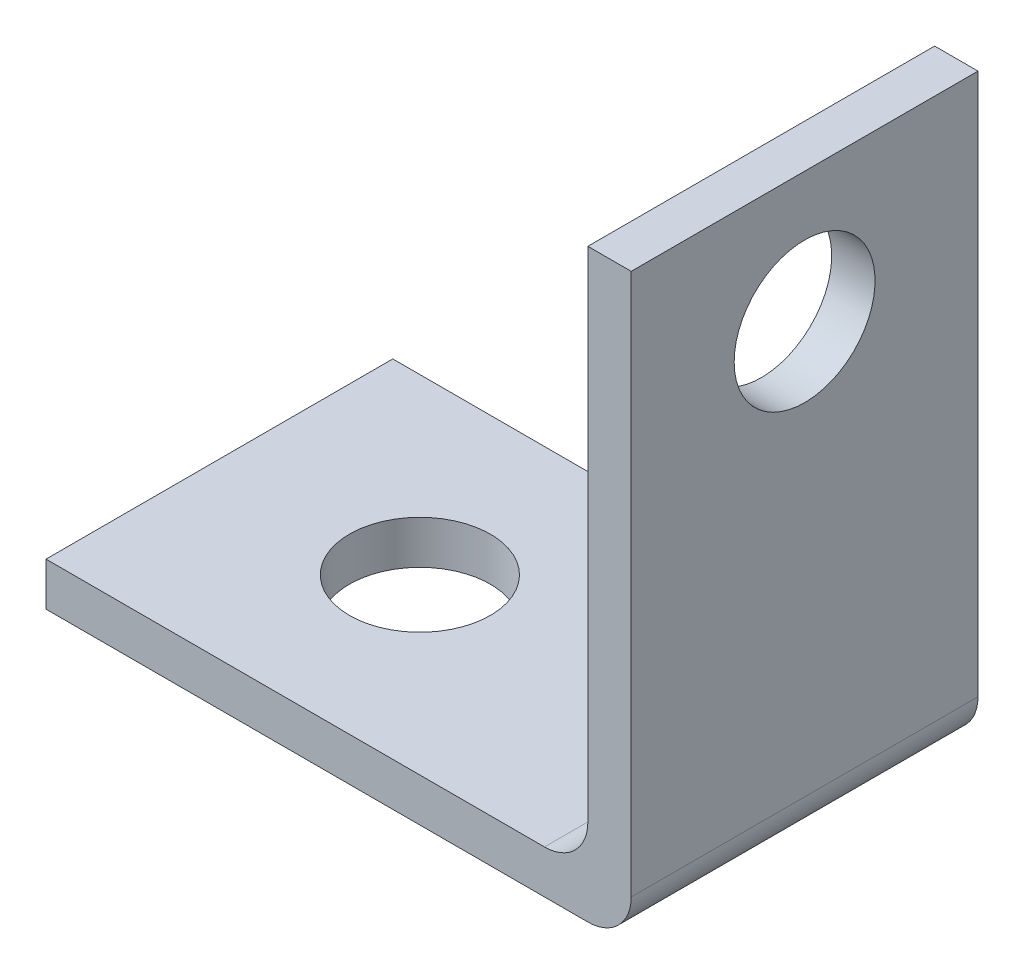
SolidWorks part; units mm, degrees
ref_plane "Alzado" through (0, 0, 0) normal (0, 0, 1) x (1, 0, 0)
ref_plane "Planta" through (0, 0, 0) normal (0, 1, 0) x (1, 0, 0)
ref_plane "Vista lateral" through (0, 0, 0) normal (1, 0, 0) x (0, 0, -1)
sketch "Croquis2" plane through (0, 0, 0) normal (1, 0, 0) x (0, 0, -1)
  line L1 (-8, 1) -> (8, 1)
  line L2 (-8, 1) -> (-8, -1)
  line L3 (-8, -1) -> (8, -1)
  line L4 (8, 1) -> (8, -1)
  line L5 (-8, 1) -> (8, -1) construction
  line L6 (-8, -1) -> (8, 1) construction
  point P0 (0, 0)
  dimension "D1" = 16
  dimension "D2" = 2
extrude "Saliente-Extruir3" add sketch "Croquis2" along normal blind 25
sketch "Croquis3" plane through (25, 0, 0) normal (1, 0, 0) x (0, 0, -1)
  line L11 (-8, -1) -> (-8, 26)
  line L12 (8, -1) -> (8, 26)
  line L13 (-8, 26) -> (8, 26)
  line L15 (8, -1) -> (8, 1)
  line L16 (8, 1) -> (-8, 1)
  line L17 (-8, 1) -> (-8, -1)
  line L18 (-8, -1) -> (8, -1)
  line L22 (-8, -1) -> (8, -1)
  point P0 (0, 0)
  dimension "D2" = 27
  dimension "D1" = 0
extrude "Saliente-Extruir4" add sketch "Croquis3" along normal blind 2
fillet "Redondeo1" radius 2 2 edges at (27, -1, 0) (25, 1, 0)
sketch "Croquis4" plane through (0, 1, 0) normal (0, 1, 0) x (1, 0, 0)
  line L1 (0, 8) -> (0, -8) construction
  circle A0 centre (9.25, 0) radius 3.25
  point P4 (6, 0)
  point P5 (0, 0)
  dimension "D1" = 6.5
  dimension "D2" = 6
extrude "Cortar-Extruir1" cut sketch "Croquis4" against normal through all
sketch "Croquis5" plane through (25, 0, 0) normal (-1, 0, 0) x (0, 0, 1)
  line L0 (-8, 26) -> (8, 26) construction
  circle A0 centre (0, 20) radius 3.25
  point P2 (0, 0)
  point P5 (0, 26)
  dimension "D1" = 6.5
  dimension "D2" = 6
extrude "Cortar-Extruir2" cut sketch "Croquis5" against normal through all
